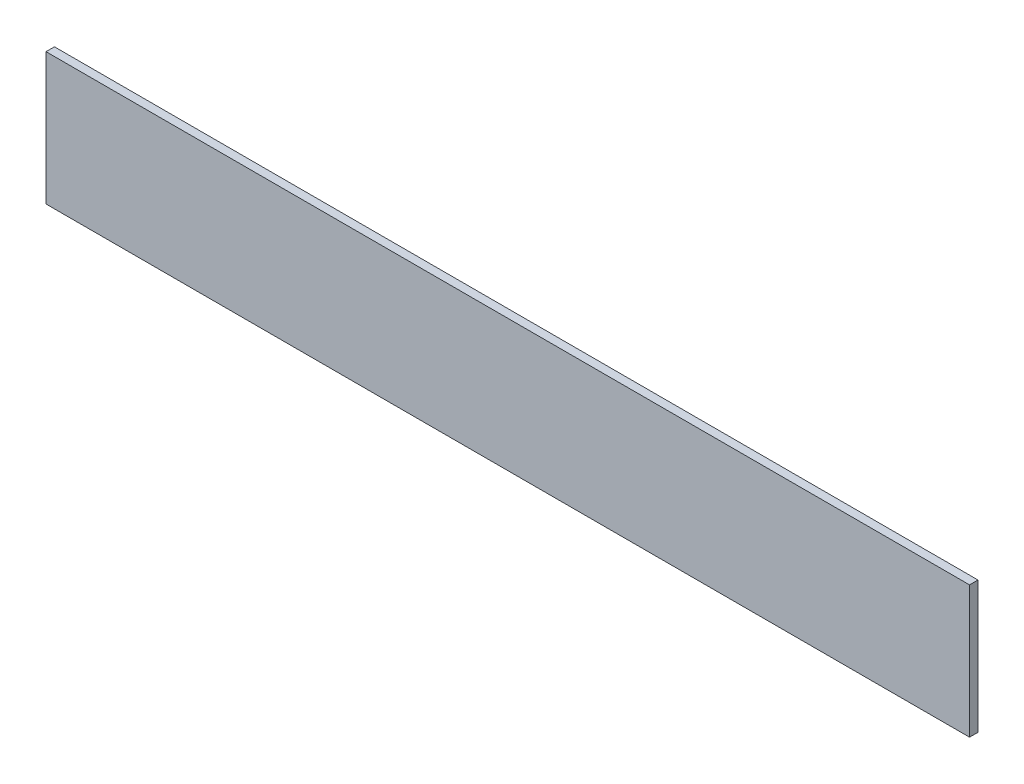
SolidWorks part; units mm, degrees
ref_plane "Front Plane" through (0, 0, 0) normal (0, 0, 1) x (1, 0, 0)
ref_plane "Top Plane" through (0, 0, 0) normal (0, 1, 0) x (1, 0, 0)
ref_plane "Right Plane" through (0, 0, 0) normal (1, 0, 0) x (0, 0, -1)
sketch "Sketch1" plane through (0, 0, 0) normal (0, 0, 1) x (1, 0, 0)
  line L1 (-87.5, 12.5) -> (87.5, 12.5)
  line L2 (-87.5, 12.5) -> (-87.5, -12.5)
  line L3 (-87.5, -12.5) -> (87.5, -12.5)
  line L4 (87.5, 12.5) -> (87.5, -12.5)
  line L5 (-87.5, 12.5) -> (87.5, -12.5) construction
  line L6 (-87.5, -12.5) -> (87.5, 12.5) construction
  point P0 (0, 0)
  dimension "D1" = 175
  dimension "D2" = 25
extrude "Boss-Extrude1" add sketch "Sketch1" along normal mid plane 1.6
